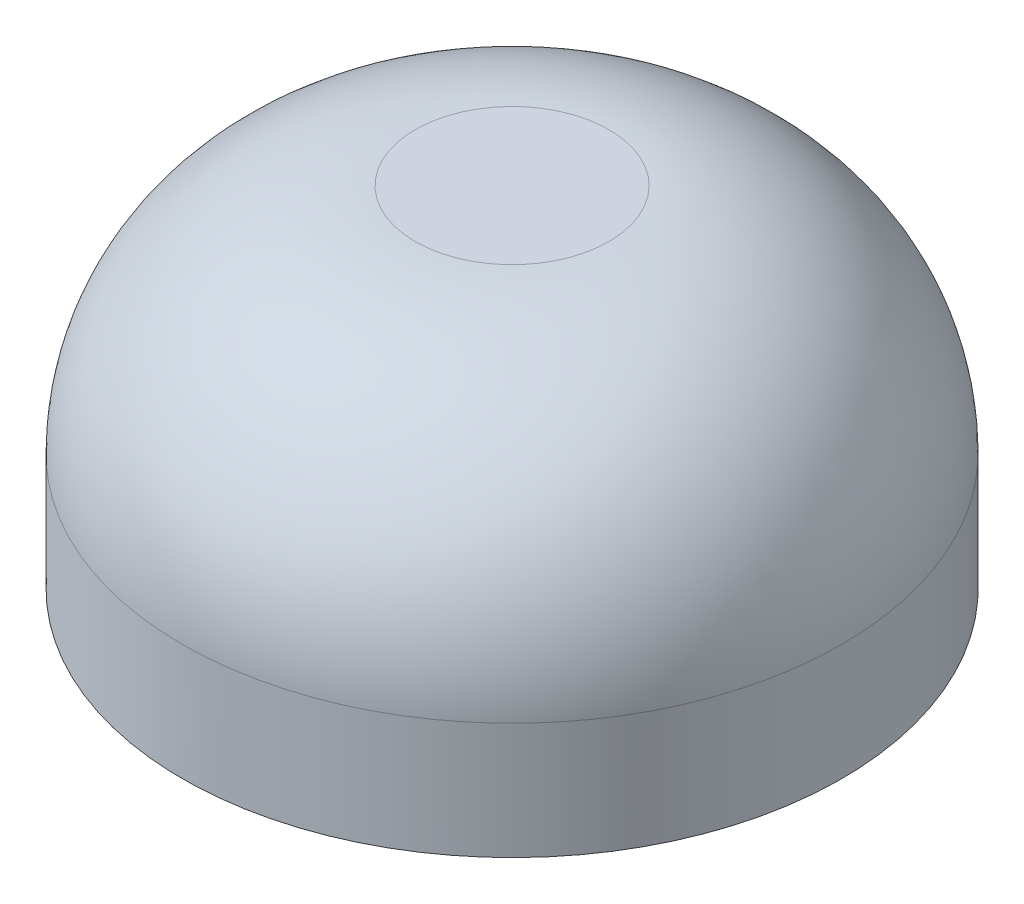
SolidWorks part; units mm, degrees
ref_plane "Front Plane" through (0, 0, 0) normal (0, 0, 1) x (1, 0, 0)
ref_plane "Top Plane" through (0, 0, 0) normal (0, 1, 0) x (1, 0, 0)
ref_plane "Right Plane" through (0, 0, 0) normal (1, 0, 0) x (0, 0, -1)
sketch "Sketch1" plane through (0, 110, 0) normal (0, 1, 0) x (1, 0, 0)
  circle A0 centre (0, 0) radius 85
  dimension "D1" = 170
extrude "Boss-Extrude1" add sketch "Sketch1" along normal blind 90
fillet "Fillet1" radius 60 1 edges at (0, 200, 85)
